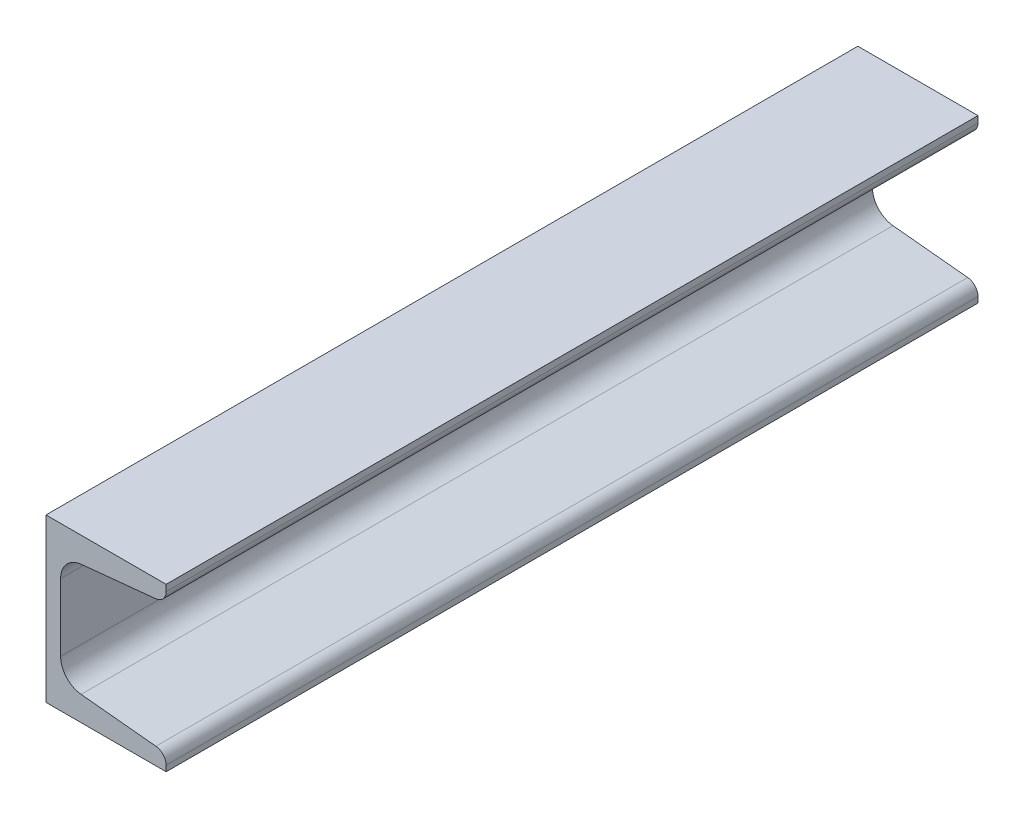
SolidWorks part; units mm, degrees
ref_plane "前视基准面" through (0, 0, 0) normal (0, 0, 1) x (1, 0, 0)
ref_plane "上视基准面" through (0, 0, 0) normal (0, 1, 0) x (1, 0, 0)
ref_plane "右视基准面" through (0, 0, 0) normal (1, 0, 0) x (0, 0, -1)
sketch "草图1" plane through (0, 0, 0) normal (0, 0, 1) x (1, 0, 0)
  line L0 (0, 0) -> (0, 50)
  line L1 (0, 0) -> (37, 0)
  line L2 (-55.9537, 25) -> (55.9537, 25) construction
  line L3 (0, 50) -> (37, 50)
  line L4 (4.5, 14.5099) -> (4.5, 35.2876)
  line L5 (16.25, -10) -> (16.25, 60) construction
  line L6 (10.8035, 7.5447) -> (33.8483, 5.2402)
  line L7 (37, 0) -> (37, 1.7575)
  line L8 (10.8035, 42.2529) -> (33.8483, 44.5574)
  line L9 (37, 48.04) -> (37, 50)
  arc A0 (10.8035, 42.2529) -> (4.5, 35.2876) centre (11.5, 35.2876) ccw
  arc A1 (4.5, 14.5099) -> (10.8035, 7.5447) centre (11.5, 14.5099) ccw
  arc A2 (33.8483, 44.5574) -> (37, 48.04) centre (33.5, 48.04) ccw
  arc A3 (37, 1.7575) -> (33.8483, 5.2402) centre (33.5, 1.7575) ccw
  point P7 (0, 25)
  point P11 (4.5, 25)
  point P14 (16.25, 25)
  point P15 (16.25, 7)
  point P17 (16.25, 43)
  point P19 (16.25, 43)
  point P20 (16.25, 7)
  point P23 (16.25, 43)
  dimension "D5" = 7
  dimension "D6" = 7
  dimension "D7" = 3.5
  dimension "D8" = 3.5
  dimension "h" = 50
  dimension "b" = 37
  dimension "d" = 4.5
  dimension "D1" = 16.25
  dimension "D2" = 7
  dimension "D3" = 5.711
  dimension "D4" = 5.711
extrude "凸台-拉伸1" add sketch "草图1" along normal blind 250
equation "\"高度\"= 50"
equation "\"腿宽\"= 37"
equation "\"腰宽\"= 4.5"
equation "\"h@草图1\"= \"高度\""
equation "\"d@草图1\"= \"腰宽\""
equation "\"D1@草图1\"= ( \"腿宽\" - \"腰宽\" ) / 2"
equation "\"平均腿厚\"= 7"
equation "\"内圆弧半径\"= 7"
equation "\"腿端圆弧半径\"= 3.5"
equation "\"D2@草图1\"= \"平均腿厚\""
equation "\"斜度\"= atn ( 0.1 )"
equation "\"D3@草图1\"= \"斜度\""
equation "\"D4@草图1\"= \"斜度\""
equation "\"D5@草图1\"= \"内圆弧半径\""
equation "\"D6@草图1\"= \"内圆弧半径\""
equation "\"D8@草图1\"= \"腿端圆弧半径\""
equation "\"D7@草图1\"= \"腿端圆弧半径\""
equation "\"b@草图1\"= \"腿宽\""
